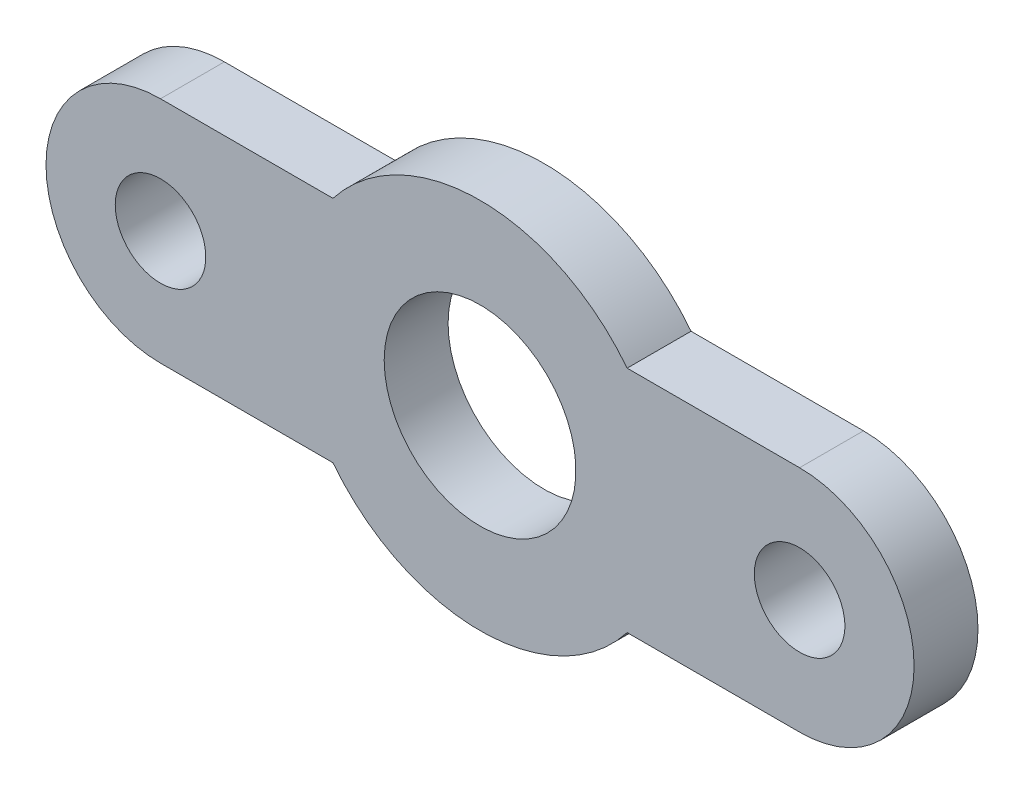
SolidWorks part; units mm, degrees
ref_plane "Front Plane" through (0, 0, 0) normal (0, 0, 1) x (1, 0, 0)
ref_plane "Top Plane" through (0, 0, 0) normal (0, 1, 0) x (1, 0, 0)
ref_plane "Right Plane" through (0, 0, 0) normal (1, 0, 0) x (0, 0, -1)
sketch "S01 - Removable two-bolt nut keeper" plane through (0, 0, 0) normal (0, 0, 1) x (1, 0, 0)
  line L0 (-12, 4.3) -> (12, 4.3)
  line L1 (12, -4.3) -> (-12, -4.3)
  arc A0 (12, 4.3) -> (12, -4.3) centre (12, 0) cw
  arc A1 (-12, -4.3) -> (-12, 4.3) centre (-12, 0) cw
  dimension "D1" = 4.3
  dimension "D2" = 12
  dimension "D3" = 12
extrude "01 - Removable two-bolt nut keeper" add sketch "S01 - Removable two-bolt nut keeper" along normal blind 2.4
sketch "S02 - Nut retaining face" plane through (0, 0, 0) normal (0, 0, 1) x (1, 0, 0)
  circle A0 centre (0, 0) radius 7
  dimension "D1" = 14
extrude "02 - Nut retaining face" add sketch "S02 - Nut retaining face" along normal blind 2.4
sketch "S03 - Screw end and two M3 fastener holes" plane through (0, 0, 0) normal (0, 0, 1) x (1, 0, 0)
  circle A0 centre (0, 0) radius 3.6
  circle A1 centre (-12, 0) radius 1.7
  circle A2 centre (12, 0) radius 1.7
  dimension "D1" = 3.4
  dimension "D2" = 3.4
  dimension "D3" = 7.2
  dimension "D4" = 12
  dimension "D5" = 12
extrude "03 - Screw end and two M3 fastener holes" cut sketch "S03 - Screw end and two M3 fastener holes" along normal blind 2.6 from offset 0.1
